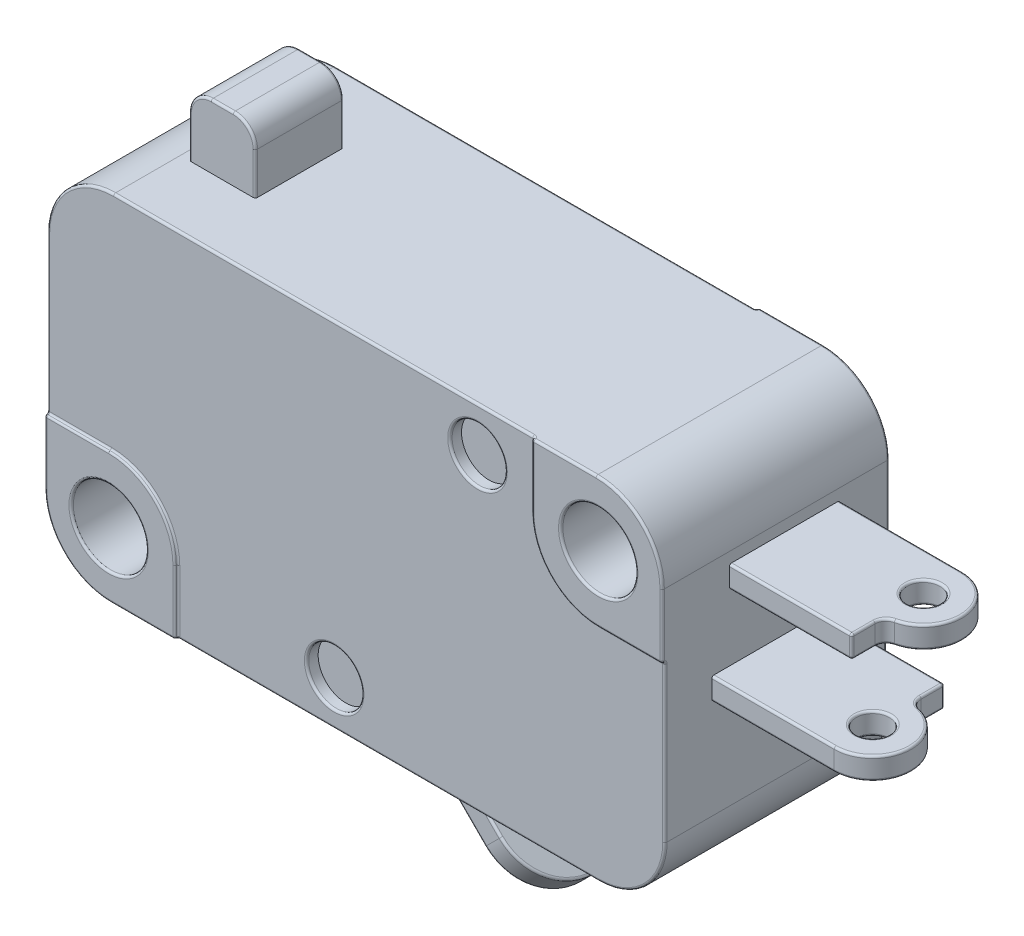
SolidWorks part; units mm, degrees
material "ABS"
ref_plane "Front Plane" through (0, 0, 0) normal (0, 0, 1) x (1, 0, 0)
ref_plane "Top Plane" through (0, 0, 0) normal (0, 1, 0) x (1, 0, 0)
ref_plane "Right Plane" through (0, 0, 0) normal (1, 0, 0) x (0, 0, -1)
sketch "Profile Sketch 1" plane through (0, 0, 0) normal (0, 0, 1) x (1, 0, 0)
  line L1 (-14, 8) -> (14, 8)
  line L2 (-14, 8) -> (-14, -8)
  line L3 (-14, -8) -> (14, -8)
  line L4 (14, 8) -> (14, -8)
  line L5 (-14, 8) -> (14, -8) construction
  line L6 (-14, -8) -> (14, 8) construction
  point P0 (0, 0)
  dimension "D1" = 28
  dimension "D2" = 16
extrude "Body 1" add sketch "Profile Sketch 1" along normal mid plane 10.05
sketch "Profile Sketch 2" plane through (0, 0, 0) normal (0, 0, 1) x (1, 0, 0)
  line L0 (-14, -8) -> (14, -8) construction
  line L1 (-14, -2.1) -> (-11.1, -2.1)
  line L2 (-14, -2.1) -> (-14, -8)
  line L3 (-14, -8) -> (-8.1, -8)
  line L4 (-8.1, -5.1) -> (-8.1, -8)
  line L5 (-14, -2.1) -> (-8.1, -8) construction
  line L6 (-14, -8) -> (-8.1, -2.1) construction
  line L7 (8.1, 8) -> (14, 8)
  line L8 (8.1, 8) -> (8.1, 5.1)
  line L9 (11.1, 2.1) -> (14, 2.1)
  line L10 (14, 8) -> (14, 2.1)
  line L11 (8.1, 8) -> (14, 2.1) construction
  line L12 (8.1, 2.1) -> (14, 8) construction
  line L13 (-14, 8) -> (-14, -8) construction
  line L14 (14, 8) -> (-14, 8) construction
  line L15 (14, -8) -> (14, 8) construction
  arc A0 (8.1, 5.1) -> (11.1, 2.1) centre (11.1, 5.1) ccw
  arc A1 (-11.1, -2.1) -> (-8.1, -5.1) centre (-11.1, -5.1) cw
  point P0 (-11.05, -5.05)
  point P5 (11.05, 5.05)
  dimension "D2" = 3
  dimension "D1" = 5.9
extrude "Body 2" add sketch "Profile Sketch 2" along normal mid plane 10.3
fillet "Body Fillet" radius 3 4 edges at (-14, -8, 0) (14, -8, 0) (14, 8, 0) (-14, 8, 0)
sketch "Profile Sketch 3" plane through (0, 0, 0) normal (0, 0, 1) x (1, 0, 0)
  circle A2 centre (11.1, 5.1) radius 1.7
  circle A3 centre (-11.1, -5.1) radius 1.7
  dimension "D1" = 3.4
extrude "Body 3" cut sketch "Profile Sketch 3" against normal through all both and the other way through all
sketch "Profile Sketch 4" plane through (0, 0, 0) normal (0, 0, 1) x (1, 0, 0)
  line L0 (8.1, 8) -> (-11, 8) construction
  line L1 (-8.1, -8) -> (11, -8) construction
  line L2 (14, -5) -> (14, 2.1) construction
  line L3 (14, 2.1) -> (14, 5) construction
  circle A0 centre (5.5, 6) radius 1.25
  circle A1 centre (-1, -6) radius 1.25
  dimension "D1" = 2.5
  dimension "D2" = 2
  dimension "D3" = 2
  dimension "D4" = 8.5
  dimension "D5" = 15
extrude "Body 4" cut sketch "Profile Sketch 4" against normal blind 0.65 from offset 5.15
mirror "Mirror Body 4" about plane through (0, 0, 0) normal (0, 0, 1) of "Body 4"
sketch "Profile Sketch 5" plane through (0, 0, 0) normal (0, 0, 1) x (1, 0, 0)
  line L0 (-10.6, 8) -> (-10.6, 9.9)
  line L1 (8.1, 8) -> (-11, 8) construction
  line L2 (-9.6, 10.9) -> (-8.6, 10.9)
  line L3 (-7.6, 9.9) -> (-7.6, 8)
  line L4 (-7.6, 8) -> (-10.6, 8)
  arc A3 (-10.6, 9.9) -> (-9.6, 10.9) centre (-9.6, 9.9) cw
  arc A4 (-8.6, 10.9) -> (-7.6, 9.9) centre (-8.6, 9.9) cw
  point P9 (-9.1, 10.9)
  dimension "D4" = 1
  dimension "D1" = 3
  dimension "D2" = 18.7
  dimension "D3" = 16
extrude "Body 5" add sketch "Profile Sketch 5" along normal mid plane 4
sketch "Profile Sketch 6" plane through (14, 0, 0) normal (1, 0, 0) x (0, 0, -1)
  line L0 (-5.025, -5) -> (-5.025, 2.1) construction
  line L1 (-2.1, 4.5) -> (2.9, 4.5)
  line L2 (-2.1, 4.5) -> (-2.1, 3.5)
  line L3 (-2.1, 3.5) -> (2.9, 3.5)
  line L4 (2.9, 4.5) -> (2.9, 3.5)
  line L5 (-2.1, 4.5) -> (2.9, 3.5) construction
  line L6 (-2.1, 3.5) -> (2.9, 4.5) construction
  line L7 (-2.9, 0.5) -> (2.1, 0.5)
  line L8 (-2.9, 0.5) -> (-2.9, -0.5)
  line L9 (-2.9, -0.5) -> (2.1, -0.5)
  line L10 (2.1, 0.5) -> (2.1, -0.5)
  line L11 (-2.9, 0.5) -> (2.1, -0.5) construction
  line L12 (-2.9, -0.5) -> (2.1, 0.5) construction
  line L13 (5.025, -5) -> (5.025, 2.1) construction
  line L14 (5.025, -8) -> (-5.025, -8) construction
  point P0 (0.4, 4)
  point P5 (-0.4, 0)
  point P10 (1.8224, 2.6761)
  dimension "D1" = 1
  dimension "D2" = 5
  dimension "D3" = 2.125
  dimension "D4" = 2.125
  dimension "D5" = 7.5
  dimension "D6" = 3
extrude "Body 6" add sketch "Profile Sketch 6" along normal blind 7.3
sketch "Profile Sketch 7" plane through (0, 0, 0) normal (0, 0, 1) x (1, 0, 0)
  line L0 (2.5, -8) -> (2.5, -9.0858)
  line L1 (-8.1, -8) -> (11, -8) construction
  line L2 (2.7929, -9.7929) -> (5.7929, -12.7929)
  line L3 (1.5, -8) -> (1.5, -9.0858)
  line L4 (2.0858, -10.5) -> (5.0858, -13.5)
  line L5 (5.0858, -13.5) -> (5.7929, -12.7929)
  line L6 (1.5, -8) -> (2.5, -8)
  line L7 (-14, -2.1) -> (-14, -5) construction
  line L8 (2.5, -8) -> (2.5, -9.5) construction
  line L9 (2.5, -9.5) -> (5.7929, -12.7929) construction
  line L10 (1.5, -8) -> (1.5, -9.9142) construction
  line L11 (1.5, -9.9142) -> (5.0858, -13.5) construction
  circle A2 centre (-11.1, -5.1) radius 1.7 construction
  arc A3 (2.5, -9.0858) -> (2.7929, -9.7929) centre (3.5, -9.0858) ccw
  arc A4 (1.5, -9.0858) -> (2.0858, -10.5) centre (3.5, -9.0858) ccw
  point P15 (2.5, -9.5)
  dimension "D6" = 1
  dimension "D7" = 2
  dimension "D1" = 135
  dimension "D2" = 8.4
  dimension "D3" = 1.5
  dimension "D4" = 15.5
  dimension "D5" = 1
extrude "Body 7" add sketch "Profile Sketch 7" along normal mid plane 5
sketch "Profile Sketch 8" plane through (0, 4.5, 0) normal (0, 1, 0) x (1, 0, 0)
  line L0 (21.3, 2.9) -> (14, 2.9) construction
  line L1 (21.3, 2.9) -> (21.3, -2.1) construction
  line L2 (19.55, -1.0437) -> (19.55, -2.9)
  line L3 (21.3, -2.9) -> (14, -2.9) construction
  line L4 (19.55, 2.9) -> (21.55, 2.9)
  line L5 (21.55, 2.9) -> (21.55, -2.9)
  line L6 (21.55, -2.9) -> (19.55, -2.9)
  circle A0 centre (19.55, 1.15) radius 0.75
  arc A1 (19.9389, -0.5562) -> (19.55, 2.9) centre (19.55, 1.15) ccw
  arc A2 (19.55, -1.0437) -> (19.9389, -0.5562) centre (20.05, -1.0437) cw
  point P17 (19.55, -0.6)
  dimension "D1" = 3.5
  dimension "D2" = 1.5
  dimension "D4" = 0.5
  dimension "D3" = 2
extrude "Body 8" cut sketch "Profile Sketch 8" against normal up to next
sketch "Profile Sketch 9" plane through (0, -0.5, 0) normal (0, -1, 0) x (1, 0, 0)
  line L0 (21.3, 2.9) -> (14, 2.9) construction
  line L1 (21.3, 2.9) -> (21.3, -2.1) construction
  line L2 (19.55, -1.0437) -> (19.55, -2.1)
  line L3 (21.3, -2.1) -> (14, -2.1) construction
  line L4 (19.55, -2.1) -> (21.55, -2.1)
  line L5 (21.55, -2.1) -> (21.55, 2.9)
  line L6 (21.55, 2.9) -> (19.55, 2.9)
  arc A0 (19.9389, -0.5562) -> (19.55, 2.9) centre (19.55, 1.15) ccw
  circle A1 centre (19.55, 1.15) radius 0.75
  arc A2 (19.55, -1.0437) -> (19.9389, -0.5562) centre (20.05, -1.0437) cw
  point P15 (19.55, -0.6)
  dimension "D1" = 3.5
  dimension "D2" = 1.5
  dimension "D4" = 0.5
  dimension "D3" = 2
extrude "Body 9" cut sketch "Profile Sketch 9" against normal up to next
sketch "Profile Sketch 10" plane through (-4.2071, -4.2071, 0) normal (-0.7071, -0.7071, 0) x (0, 0, 1)
  line L0 (2.5, -13.1421) -> (-2.5, -13.1421) construction
  line L1 (2.5, -8.8995) -> (2.5, -13.1421) construction
  line L2 (-2.5, -8.8995) -> (-2.5, -13.1421) construction
  line L3 (-2.5, -10.6421) -> (-2.5, -13.435)
  line L4 (-5.025, -13.435) -> (5.025, -13.435) construction
  line L5 (-2.5, -13.435) -> (2.5, -13.435)
  line L6 (2.5, -13.435) -> (2.5, -10.6421)
  arc A0 (-2.5, -10.6421) -> (2.5, -10.6421) centre (0, -10.6421) ccw
  circle A1 centre (0, -10.6421) radius 0.75
  dimension "D1" = 1.5
extrude "Body 10" cut sketch "Profile Sketch 10" against normal up to next
fillet "Production Fillet 1" radius 0.1 42 edges at (1.5, -8.5429, 2.5) (1.6522, -9.8512, 2.5) (2.7019, -11.1161, 2.5) (1.5, -8.5429, -2.5) (1.6522, -9.8512, -2.5) (2.7019, -11.1161, -2.5) (2.5, -8.5429, -2.5) (2.5761, -9.4685, -2.5) (3.409, -10.409, -2.5) (2.5, -8.5429, 2.5) (2.5761, -9.4685, 2.5) (3.409, -10.409, 2.5) (16.775, -0.5, 2.9) (19.55, -0.5, -1.5719) (19.6591, -0.5, -0.7319) (19.55, 0.5, -1.5719) (19.6591, 0.5, -0.7319) (16.775, 0.5, 2.9) (16.775, 4.5, -2.9) (19.55, 4.5, 1.5719) (19.6591, 4.5, 0.7319) (19.55, 3.5, 1.5719) (19.6591, 3.5, 0.7319) (16.775, 3.5, -2.9) (5.0858, -13.5, 0) (5.7929, -12.7929, 0) (4.5555, -11.5555, 0) (3.8483, -12.2626, 0) (19.55, 3.5, -0.4) (19.55, 4.5, -0.4) (19.55, 0.5, 0.4) (19.55, -0.5, 0.4) (21.289, -0.5, 1.3457) (21.289, 0.5, 1.3457) (21.289, 4.5, -1.3457) (21.289, 3.5, -1.3457) (16.775, -0.5, -2.1) (16.775, 0.5, -2.1) (19.55, 0, -2.1) (16.775, 3.5, 2.1) (16.775, 4.5, 2.1) (19.55, 4, 2.1)
fillet "Production Fillet 2" radius 0.1 10 edges at (-7.6, 8.95, 2) (-7.8929, 10.6071, 2) (-10.6, 8.95, 2) (-10.3071, 10.6071, 2) (-7.6, 8.95, -2) (-7.8929, 10.6071, -2) (-10.6, 8.95, -2) (-10.3071, 10.6071, -2) (-9.1, 10.9, 2) (-9.1, 10.9, -2)
fillet "Production Fillet 3" radius 0.1 36 edges at (14, 2.1, -5.0875) (8.1, 8, -5.0875) (-14, -2.1, -5.0875) (-8.1, -8, -5.0875) (-8.1, -8, 5.0875) (-14, -2.1, 5.0875) (8.1, 8, 5.0875) (14, 2.1, 5.0875) (12.55, 2.1, -5.025) (8.9787, 2.9787, -5.025) (8.1, 6.55, -5.025) (-1.45, 8, -5.025) (-13.1213, 7.1213, -5.025) (-14, 1.45, -5.025) (-12.55, -2.1, -5.025) (-8.9787, -2.9787, -5.025) (-8.1, -6.55, -5.025) (1.45, -8, -5.025) (13.1213, -7.1213, -5.025) (14, -1.45, -5.025) (0.25, -6, -5.025) (6.75, 6, -5.025) (-8.1, -6.55, 5.025) (-8.9787, -2.9787, 5.025) (-12.55, -2.1, 5.025) (-14, 1.45, 5.025) (-13.1213, 7.1213, 5.025) (-1.45, 8, 5.025) (8.1, 6.55, 5.025) (8.9787, 2.9787, 5.025) (12.55, 2.1, 5.025) (14, -1.45, 5.025) (13.1213, -7.1213, 5.025) (1.45, -8, 5.025) (0.25, -6, 5.025) (6.75, 6, 5.025)
fillet "Prodution Fillet 4" radius 0.1 36 edges at (13.1213, 7.1213, 5.15) (14, 3.6, 5.15) (13.9707, 2.1293, 5.15) (12.5, 2.1, 5.15) (8.9787, 2.9787, 5.15) (8.1, 6.5, 5.15) (8.1293, 7.9707, 5.15) (9.6, 8, 5.15) (12.8, 5.1, 5.15) (-13.1213, -7.1213, 5.15) (-14, -3.6, 5.15) (-13.9707, -2.1293, 5.15) (-12.5, -2.1, 5.15) (-8.9787, -2.9787, 5.15) (-8.1, -6.5, 5.15) (-8.1293, -7.9707, 5.15) (-9.6, -8, 5.15) (-9.4, -5.1, 5.15) (13.1213, 7.1213, -5.15) (9.6, 8, -5.15) (8.1293, 7.9707, -5.15) (8.1, 6.5, -5.15) (8.9787, 2.9787, -5.15) (12.5, 2.1, -5.15) (13.9707, 2.1293, -5.15) (14, 3.6, -5.15) (12.8, 5.1, -5.15) (-13.1213, -7.1213, -5.15) (-9.6, -8, -5.15) (-8.1293, -7.9707, -5.15) (-8.1, -6.5, -5.15) (-8.9787, -2.9787, -5.15) (-12.5, -2.1, -5.15) (-13.9707, -2.1293, -5.15) (-14, -3.6, -5.15) (-9.4, -5.1, -5.15)
